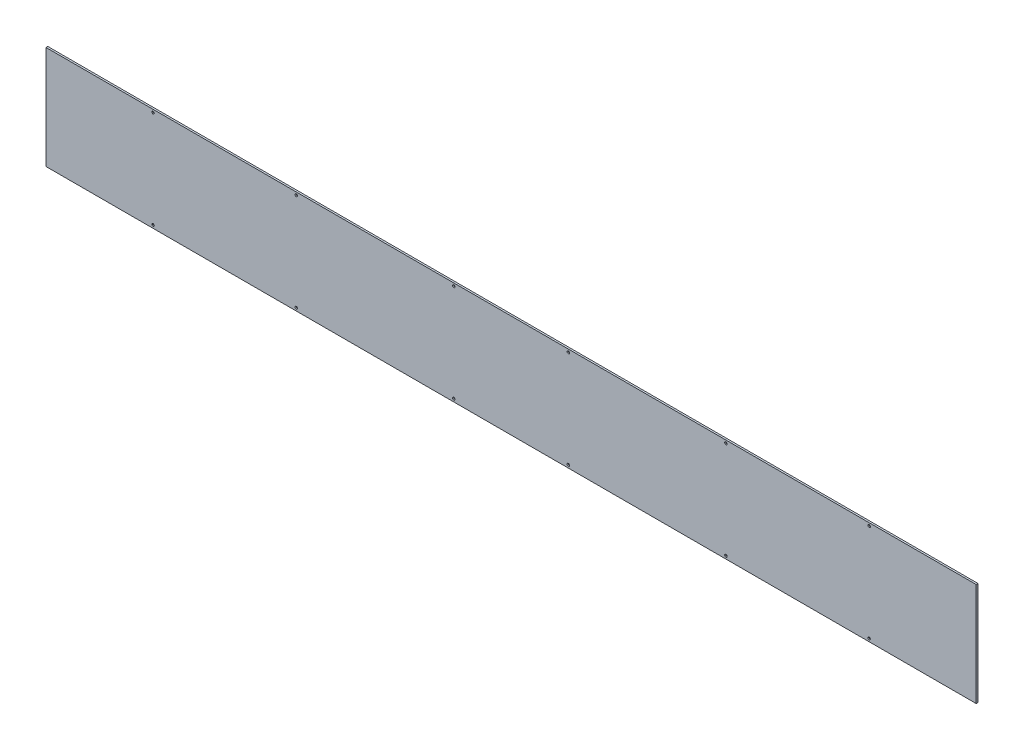
SolidWorks part; units mm, degrees
ref_plane "Alzado" through (0, 0, 0) normal (0, 0, 1) x (1, 0, 0)
ref_plane "Planta" through (0, 0, 0) normal (0, 1, 0) x (1, 0, 0)
ref_plane "Vista lateral" through (0, 0, 0) normal (1, 0, 0) x (0, 0, -1)
sketch "Sketch1" plane through (0, 0, 0) normal (0, 0, 1) x (1, 0, 0)
  line L0 (3247.5, -360) -> (3247.5, 360)
  line L5 (-3247.5, 360) -> (-3247.5, -360)
  line L6 (3247.5, 360) -> (-3247.5, 360)
  line L39 (-3247.5, -360) -> (3247.5, -360)
  point P0 (0, 0)
  point P1 (-3247.5, 0)
  point P4 (3174.3951, 360)
  point P7 (0, 360)
  dimension "D1" = 6495
  dimension "D2" = 720
extrude "Boss-Extrude1" add sketch "Sketch1" along normal blind 12.7
hole_wizard "CSK for M8 Flat Head Machine Screw1" positions "Sketch2" profile "Sketch4" countersink size "M8" standard "ANSI Metric"
sketch "Sketch2" plane through (0, 0, 12.7) normal (0, 0, 1) x (1, 0, 0)
  line L0 (-3247.5, -360) -> (3247.5, -360) construction
  line L1 (3247.5, 360) -> (-3247.5, 360) construction
  point P0 (-2500, 340)
  point P2 (-1500, 340)
  point P4 (400, 340)
  point P6 (1500, 340)
  point P8 (2500, 340)
  point P10 (2500, -340)
  point P12 (1500, -340)
  point P14 (400, -340)
  point P16 (-1500, -340)
  point P18 (-2500, -340)
  point P24 (-400, 340)
  point P26 (-400, -340)
  dimension "D1" = 20
  dimension "D2" = 20
  dimension "D3" = 400
  dimension "D4" = 800
  dimension "D5" = 3000
  dimension "D6" = 1500
  dimension "D7" = 2500
  dimension "D8" = 5000
sketch "Sketch4" plane through (-2500, 340, 12.7) normal (1, 0, 0) x (0, -1, 0)
  line L0 (0, 0) -> (0, 32.5236)
  line L1 (0, 32.5236) -> (4.2, 30)
  line L2 (4.2, 30) -> (4.2, 4.45)
  line L3 (4.2, 4.45) -> (8.65, 0)
  line L5 (8.65, 0) -> (0, 0)
  line L6 (-4.2, 4.45) -> (-8.65, 0) construction
  line L10 (0, 32.5236) -> (-4.2, 30) construction
  line L11 (0, -6.35) -> (0, 107.95) construction
  dimension "Hole Dia." = 8.4
  dimension "Hole Depth" = 30
  dimension "Near C'Sink Dia." = 17.3
  dimension "Near C'Sink Angle" = 90
  dimension "Drill Angle" = 118
